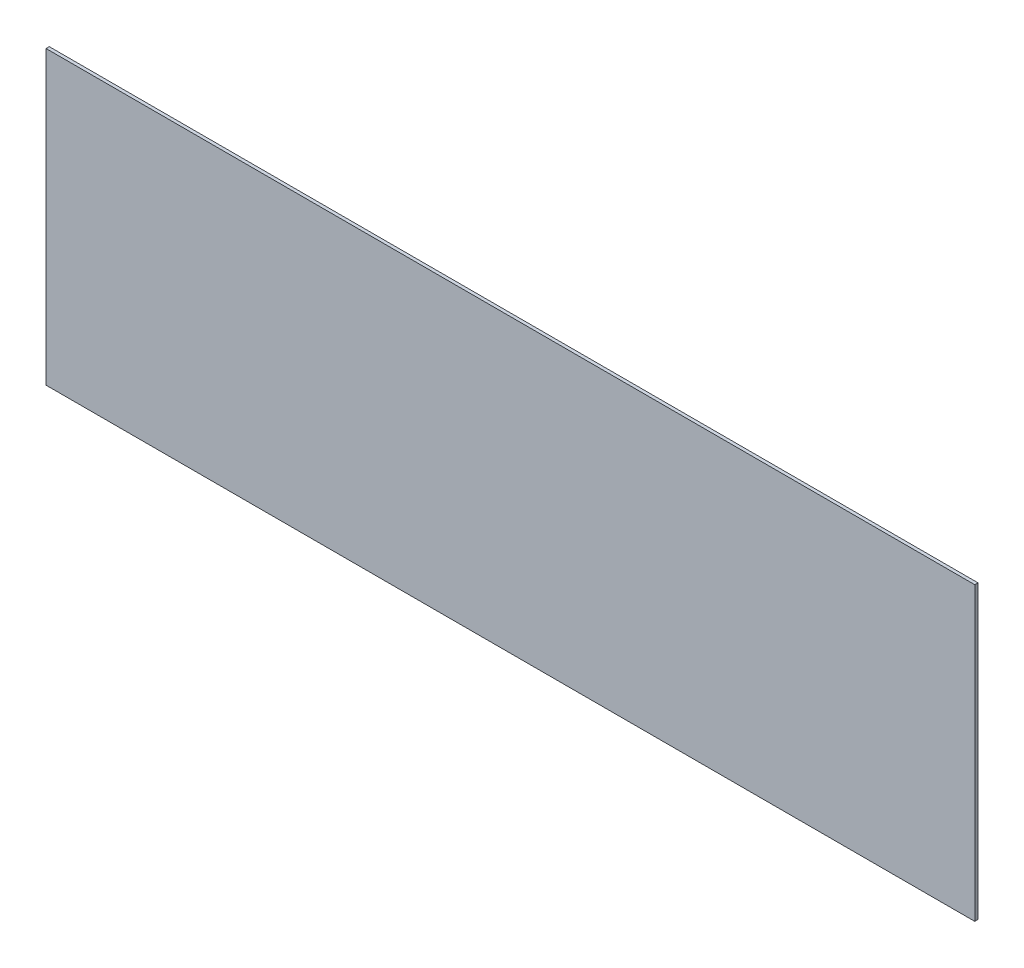
SolidWorks part; units mm, degrees
ref_plane "Front Plane" through (0, 0, 0) normal (0, 0, 1) x (1, 0, 0)
ref_plane "Top Plane" through (0, 0, 0) normal (0, 1, 0) x (1, 0, 0)
ref_plane "Right Plane" through (0, 0, 0) normal (1, 0, 0) x (0, 0, -1)
sketch "Sketch1" plane through (0, 0, 0) normal (0, 0, 1) x (1, 0, 0)
  line L1 (-430, -135) -> (430, -135)
  line L2 (-430, -135) -> (-430, 135)
  line L3 (-430, 135) -> (430, 135)
  line L4 (430, -135) -> (430, 135)
  line L5 (-430, -135) -> (430, 135) construction
  line L6 (-430, 135) -> (430, -135) construction
  point P0 (0, 0)
  dimension "D1" = 860
  dimension "D2" = 270
extrude "Boss-Extrude1" add sketch "Sketch1" along normal blind 3
